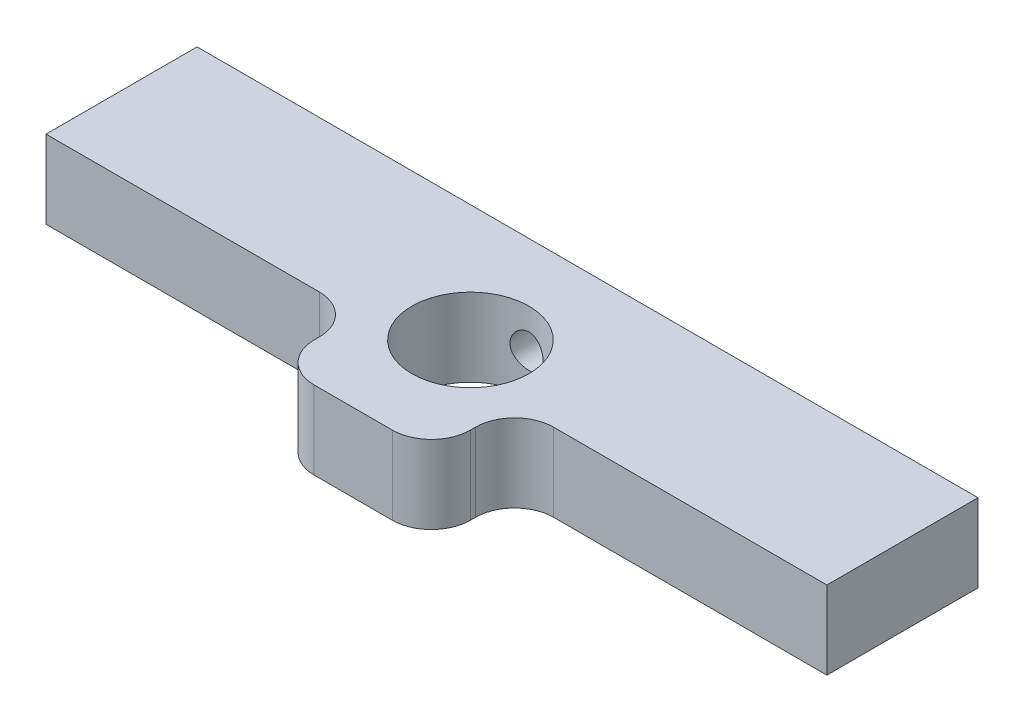
SolidWorks part; units mm, degrees
ref_plane "Front Plane" through (0, 0, 0) normal (0, 0, 1) x (1, 0, 0)
ref_plane "Top Plane" through (0, 0, 0) normal (0, 1, 0) x (1, 0, 0)
ref_plane "Right Plane" through (0, 0, 0) normal (1, 0, 0) x (0, 0, -1)
sketch "Sketch1" plane through (0, 0, 0) normal (0, 1, 0) x (1, 0, 0)
  line L1 (-31.75, -9.525) -> (31.75, -9.525)
  line L2 (-31.75, -9.525) -> (-31.75, 9.525)
  line L3 (-31.75, 9.525) -> (31.75, 9.525)
  line L4 (31.75, -9.525) -> (31.75, 9.525)
  line L5 (-31.75, -9.525) -> (31.75, 9.525) construction
  line L6 (-31.75, 9.525) -> (31.75, -9.525) construction
  circle A0 centre (0, 0) radius 4.7625
  dimension "D1" = 9.525
  dimension "D2" = 31.75
  dimension "D3" = 19.05
extrude "Boss-Extrude1" add sketch "Sketch1" along normal blind 6.35
sketch "Sketch2" plane through (0, 0, -9.525) normal (0, 0, -1) x (-1, 0, 0)
  line L0 (31.75, 6.35) -> (31.75, 0) construction
  line L1 (0, 55) -> (0, -55) construction
  point P0 (0, 3.175)
  point P4 (31.75, 3.175)
hole_wizard "#6-32 Tapped Hole1" positions "Sketch3" profile "Sketch4" tap size "#6-32" standard "ANSI Inch"
sketch "Sketch3" plane through (0, 0, -9.525) normal (0, 0, -1) x (-1, 0, 0)
  point P0 (0, 3.175)
sketch "Sketch4" plane through (0, 3.175, -9.525) normal (1, 0, 0) x (0, 1, 0)
  line L0 (0, 0) -> (0, 4.7625)
  line L1 (0, 4.7625) -> (1.3525, 4.7625)
  line L2 (1.3525, 4.7625) -> (1.3525, 0)
  line L5 (1.3525, 0) -> (0, 0)
  line L11 (0, -6.35) -> (0, 107.95) construction
  dimension "Thru Tap Drill Dia." = 2.7051
  dimension "Thru Tap Drill Depth" = 4.7625
cosmetic thread "Hole Thread1" parameters "D2"=3.5052
sketch "Sketch5" plane through (0, 6.35, 0) normal (0, 1, 0) x (1, 0, 0)
  line L0 (31.75, -2.7623) -> (-31.75, -2.7623) construction
  line L1 (-6.35, -2.7623) -> (-6.35, -9.525)
  line L2 (-31.75, 9.525) -> (-31.75, -9.525) construction
  line L3 (31.75, -9.525) -> (31.75, 9.525) construction
  line L6 (-31.75, -9.525) -> (31.75, -9.525) construction
  line L7 (0, -3.4925) -> (0, 3.4925) construction
  line L12 (-3.4925, 0) -> (3.4925, 0) construction
  line L13 (-6.35, -9.525) -> (6.35, -9.525)
  line L14 (6.35, -9.525) -> (6.35, -2.7623)
  line L15 (-6.35, -9.525) -> (-31.75, -9.525)
  line L16 (-31.75, -9.525) -> (-31.75, -2.7623)
  line L17 (6.35, -9.525) -> (31.75, -9.525)
  line L18 (31.75, -9.525) -> (31.75, -2.7623)
  line L19 (31.75, -2.7623) -> (6.35, -2.7623)
  line L20 (-6.35, -2.7623) -> (-31.75, -2.7623)
  point P4 (0, -9.525)
  point P15 (0, -9.525)
  dimension "D1" = 2.7623
  dimension "D2" = 6.35
extrude "Cut-Extrude1" cut sketch "Sketch5" against normal up to next
fillet "Fillet1" radius 3.175 4 edges at (6.35, 3.175, 2.7623) (6.35, 3.175, 9.525) (-6.35, 3.175, 9.525) (-6.35, 3.175, 2.7623)
